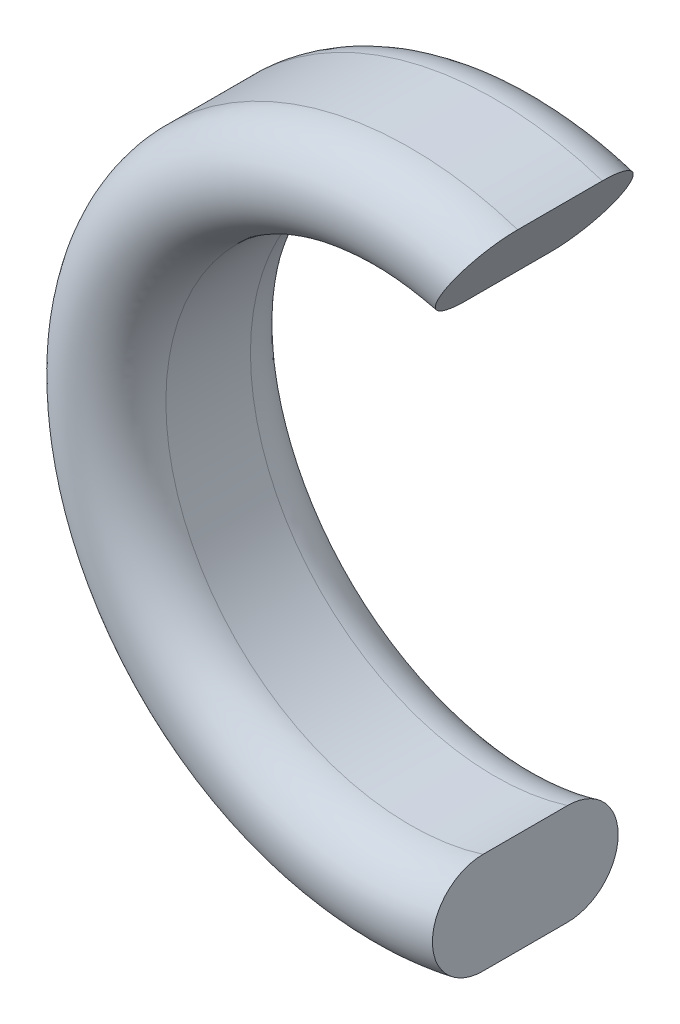
SolidWorks part; units mm, degrees
ref_plane "Ön Düzlem" through (0, 0, 0) normal (0, 0, 1) x (1, 0, 0)
ref_plane "Üst Düzlem" through (0, 0, 0) normal (0, 1, 0) x (1, 0, 0)
ref_plane "Sağ Düzlem" through (0, 0, 0) normal (1, 0, 0) x (0, 0, -1)
sketch "Çizim1" plane through (0, 0, 0) normal (0, 0, 1) x (1, 0, 0)
  arc A0 (0, 0) -> (1.4814, 93.5204) centre (-12.037, 46.9626) cw
  point P3 (0, 0)
  point P5 (0, 0)
  point P6 (0, 0)
  point P7 (0.748, 103.9855)
  point P8 (2.5613, 95.9195)
sketch "Çizim2" plane through (0, 0, 0) normal (1, 0, 0) x (0, 0, -1)
  line L0 (-6.9967, 0) -> (6.9967, 0) construction
  line L1 (-6.9967, 8.3657) -> (6.9967, 8.3657)
  line L2 (-6.9967, -8.3657) -> (6.9967, -8.3657)
  arc A0 (-6.9967, 8.3657) -> (-6.9967, -8.3657) centre (-6.9967, 0) ccw
  arc A1 (6.9967, -8.3657) -> (6.9967, 8.3657) centre (6.9967, 0) ccw
  point P2 (0, 0)
sweep "Süpür2" add profiles "Çizim2" path "Çizim1"
